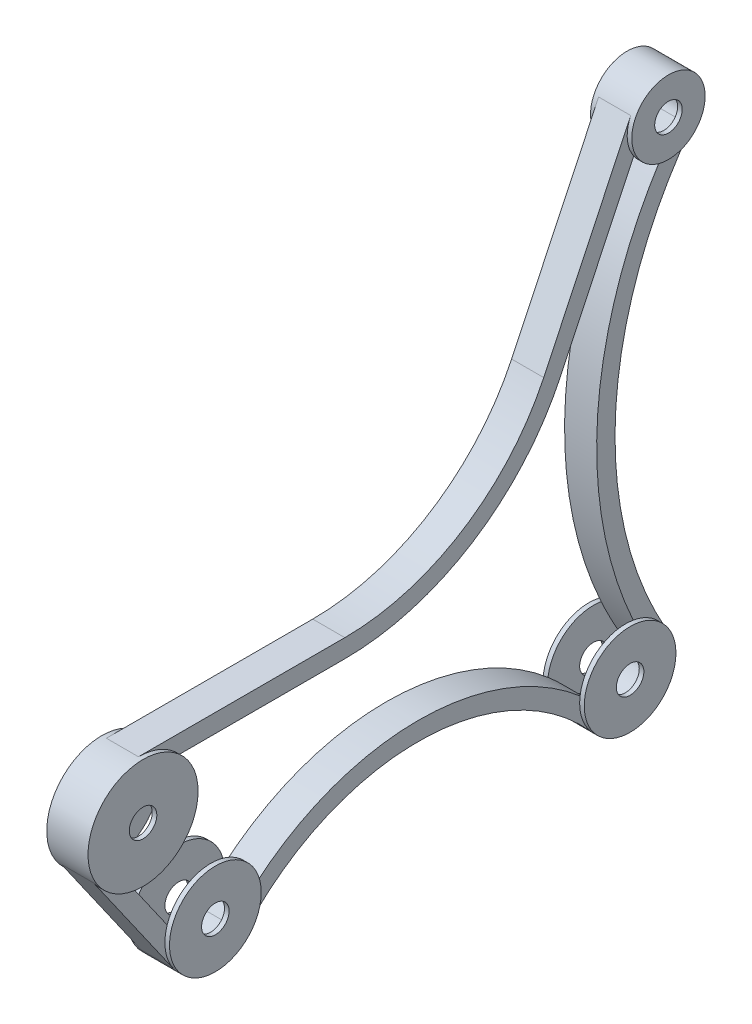
SolidWorks part; units mm, degrees
ref_plane "Front Plane" through (0, 0, 0) normal (0, 0, 1) x (1, 0, 0)
ref_plane "Top Plane" through (0, 0, 0) normal (0, 1, 0) x (1, 0, 0)
ref_plane "Right Plane" through (0, 0, 0) normal (1, 0, 0) x (0, 0, -1)
sketch "Sketch1" plane through (0, 0, 0) normal (1, 0, 0) x (0, 0, -1)
  line L0 (0, 0) -> (1249.8026, 0) construction
  line L1 (1249.8026, 0) -> (1656.0017, 856.3429) construction
  line L3 (1828.8, 751.471) -> (1828.8, -609.6) construction
  line L4 (1828.8, -609.6) -> (426.8465, -609.6) construction
  line L5 (426.8465, -609.6) -> (0, 0) construction
  line L6 (292.7577, 0) -> (864.2577, 0)
  line L7 (1415.0361, 348.3429) -> (1656.0017, 856.3429)
  line L8 (167.9189, -239.813) -> (388.9262, -555.4442)
  line L9 (292.7577, -50.8) -> (864.2577, -50.8)
  line L10 (1460.9343, 326.5714) -> (1701.8999, 834.5714)
  line L11 (209.5318, -210.6754) -> (430.5391, -526.3065)
  arc A2 (1656.0017, 856.3429) -> (1828.8, 751.471) centre (1747.7981, 812.8) cw
  arc A5 (864.2577, 0) -> (1415.0361, 348.3429) centre (864.2577, 609.6) ccw
  arc A6 (167.9189, -239.813) -> (292.7577, 0) centre (292.7577, -152.4) cw
  arc A7 (1546.4466, -566.7431) -> (1751.9712, -419.8216) centre (1641.5725, -482.6) ccw
  arc A8 (388.9262, -555.4442) -> (588.0844, -566.7431) centre (492.9585, -482.6) ccw
  arc A9 (588.0844, -566.7431) -> (1546.4466, -566.7431) centre (1067.2655, -990.6) cw
  arc A10 (1751.9712, -419.8216) -> (1828.8, 751.471) centre (2679.3204, 107.5166) cw
  arc A11 (864.2577, -50.8) -> (1460.9343, 326.5714) centre (864.2577, 609.6) ccw
  arc A12 (1701.8999, 834.5714) -> (1788.299, 782.1355) centre (1747.7981, 812.8) cw
  arc A13 (1707.8117, -444.933) -> (1788.299, 782.1355) centre (2679.3204, 107.5166) cw
  arc A14 (1584.4969, -533.0859) -> (1707.8117, -444.933) centre (1641.5725, -482.6) ccw
  arc A15 (550.0341, -533.0859) -> (1584.4969, -533.0859) centre (1067.2655, -990.6) cw
  arc A16 (430.5391, -526.3065) -> (550.0341, -533.0859) centre (492.9585, -482.6) ccw
  arc A17 (209.5318, -210.6754) -> (292.7577, -50.8) centre (292.7577, -152.4) cw
  point P2 (0, 0)
  point P22 (1862.9707, -424.545)
  point P23 (0, 0)
  dimension "D1" = 609.6
  dimension "D5" = 609.6
  dimension "D6" = 152.4
  dimension "D7" = 101.6
  dimension "D8" = 127
  dimension "D9" = 127
  dimension "D10" = 1066.8
  dimension "D2" = 1828.8
  dimension "D3" = 1524
  dimension "D4" = 762
  dimension "D11" = 125
  dimension "D12" = 571.5
  dimension "D13" = 508
  dimension "D14" = 50.8
extrude "Boss-Extrude1" add sketch "Sketch1" against normal mid plane 88.9
sketch "Sketch2" plane through (44.45, 0, 0) normal (1, 0, 0) x (0, 0, -1)
  line L1 (167.9189, -239.813) -> (388.9262, -555.4442) construction
  line L2 (864.2577, 0) -> (292.7577, 0) construction
  circle A0 centre (492.9585, -482.6) radius 127
  arc A4 (388.9262, -555.4442) -> (588.0844, -566.7431) centre (492.9585, -482.6) ccw construction
  arc A5 (1546.4466, -566.7431) -> (588.0844, -566.7431) centre (1067.2655, -990.6) ccw construction
  circle A6 centre (292.7577, -152.4) radius 152.4
  arc A7 (292.7577, 0) -> (167.9189, -239.813) centre (292.7577, -152.4) ccw construction
  circle A8 centre (1641.5725, -482.6) radius 127
  arc A9 (1828.8, 751.471) -> (1751.9712, -419.8216) centre (2679.3204, 107.5166) ccw construction
  circle A10 centre (1747.7981, 812.8) radius 101.6
  circle A11 centre (292.7577, -152.4) radius 38.1
  circle A12 centre (492.9585, -482.6) radius 38.1
  circle A13 centre (1641.5725, -482.6) radius 38.1
  circle A14 centre (1747.7981, 812.8) radius 38.1
  dimension "D1" = 76.2
extrude "Boss-Extrude2" add sketch "Sketch2" along normal blind 12.7
mirror "Mirror1" about plane through (0, 0, 0) normal (1, 0, 0) of "Boss-Extrude2"
